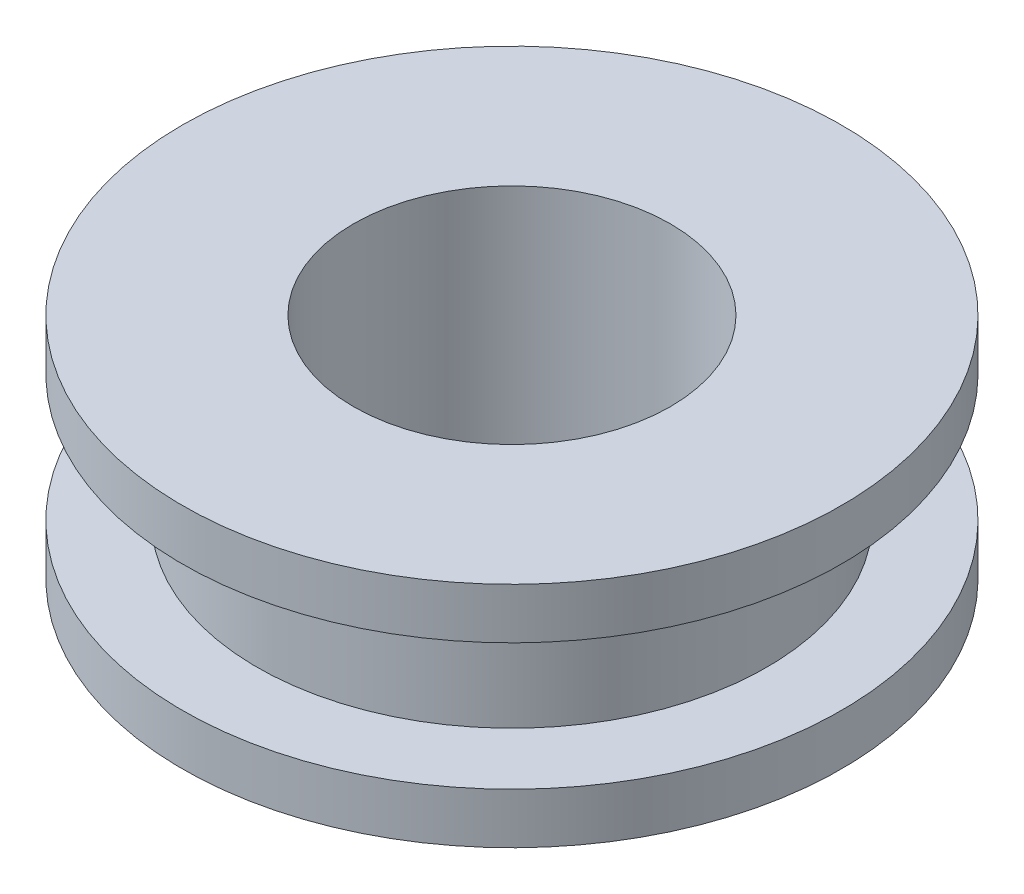
SolidWorks part; units mm, degrees
ref_plane "Front Plane" through (0, 0, 0) normal (0, 0, 1) x (1, 0, 0)
ref_plane "Top Plane" through (0, 0, 0) normal (0, 1, 0) x (1, 0, 0)
ref_plane "Right Plane" through (0, 0, 0) normal (1, 0, 0) x (0, 0, -1)
sketch "Sketch2" plane through (0, 0, 0) normal (0, 0, 1) x (1, 0, 0)
  line L0 (0, 0) -> (52, 0)
  line L1 (52, 0) -> (52, 8)
  line L2 (52, 8) -> (40.2167, 8)
  line L3 (40.2167, 8) -> (40.2167, 28)
  line L4 (40.2167, 28) -> (52, 28)
  line L5 (52, 28) -> (52, 36)
  line L6 (52, 36) -> (0, 36)
  line L7 (0, 36) -> (0, 0)
  dimension "D1" = 52
  dimension "D2" = 8
  dimension "D3" = 36
  dimension "D4" = 8
revolve "Revolve1" add sketch "Sketch2" angle 360 about L7
sketch "Sketch3" plane through (0, 36, 0) normal (0, 1, 0) x (1, 0, 0)
  circle A0 centre (0, 0) radius 25
extrude "Cut-Extrude1" cut sketch "Sketch3" against normal blind 10
sketch "Sketch5" plane through (0, 26, 0) normal (0, 1, 0) x (1, 0, 0)
  circle A0 centre (0, 0) radius 25
extrude "Cut-Extrude2" cut sketch "Sketch5" against normal blind 36
